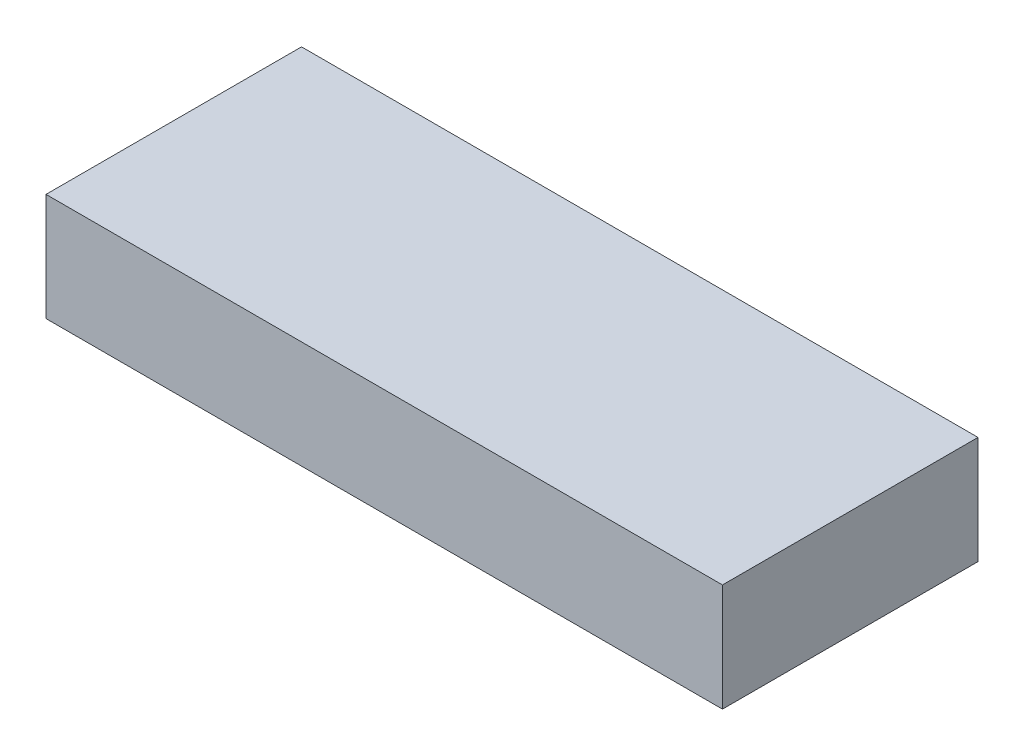
SolidWorks part; units mm, degrees
ref_plane "Front Plane" through (0, 0, 0) normal (0, 0, 1) x (1, 0, 0)
ref_plane "Top Plane" through (0, 0, 0) normal (0, 1, 0) x (1, 0, 0)
ref_plane "Right Plane" through (0, 0, 0) normal (1, 0, 0) x (0, 0, -1)
sketch "Sketch1" plane through (0, 0, 0) normal (0, 1, 0) x (1, 0, 0)
  line L1 (-51.7447, 7.883) -> (-1.4447, 7.883)
  line L2 (-51.7447, 7.883) -> (-51.7447, -11.117)
  line L3 (-51.7447, -11.117) -> (-1.4447, -11.117)
  line L4 (-1.4447, 7.883) -> (-1.4447, -11.117)
  dimension "D1" = 19
  dimension "D2" = 50.3
extrude "Boss-Extrude1" add sketch "Sketch1" along normal blind 8
